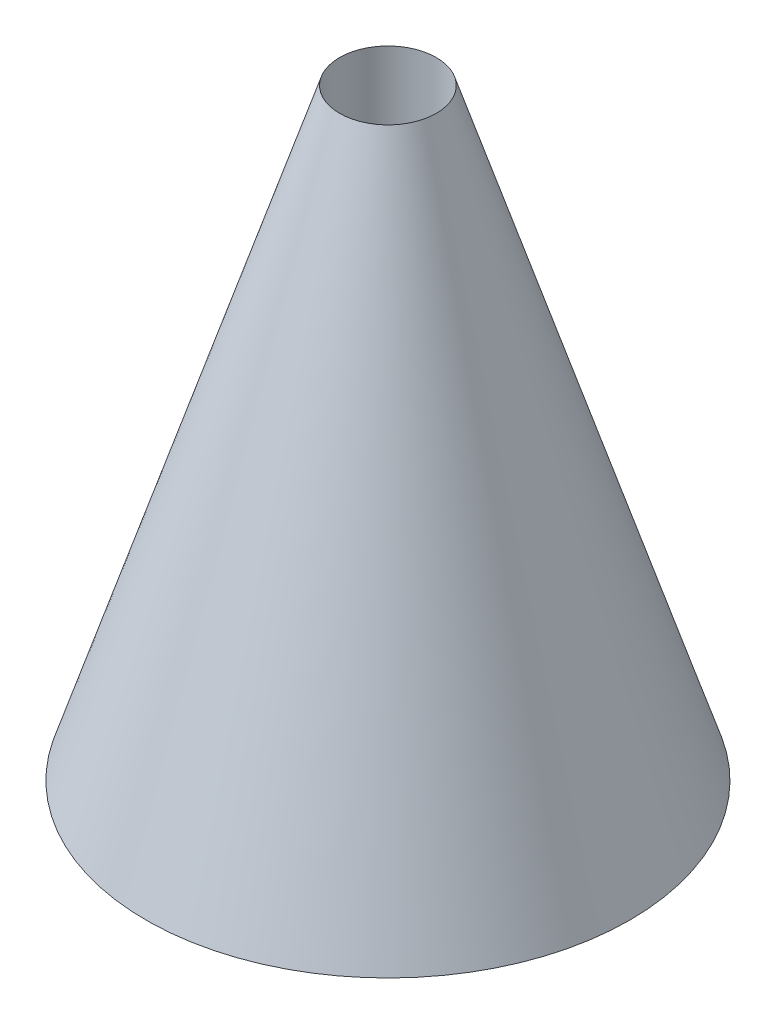
SolidWorks part; units mm, degrees
ref_plane "Front Plane" through (0, 0, 0) normal (0, 0, 1) x (1, 0, 0)
ref_plane "Top Plane" through (0, 0, 0) normal (0, 1, 0) x (1, 0, 0)
ref_plane "Right Plane" through (0, 0, 0) normal (1, 0, 0) x (0, 0, -1)
sketch "Sketch1" plane through (0, 0, 0) normal (0, 0, 1) x (1, 0, 0)
  line L0 (0, 0) -> (12.7, 0)
  line L1 (12.7, 0) -> (1.27, 35.56)
  line L2 (1.27, 35.56) -> (0, 35.56)
  line L3 (0, 35.56) -> (0, 0)
  dimension "D1" = 35.56
  dimension "D2" = 1.27
  dimension "D3" = 12.7
revolve "Revolve1" add sketch "Sketch1" angle 360 about L3
sketch "Sketch2" plane through (0, 35.56, 0) normal (0, 1, 0) x (1, 0, 0)
  circle A0 centre (0, 0) radius 2.54
extrude "Cut-Extrude1" cut sketch "Sketch2" against normal through all
